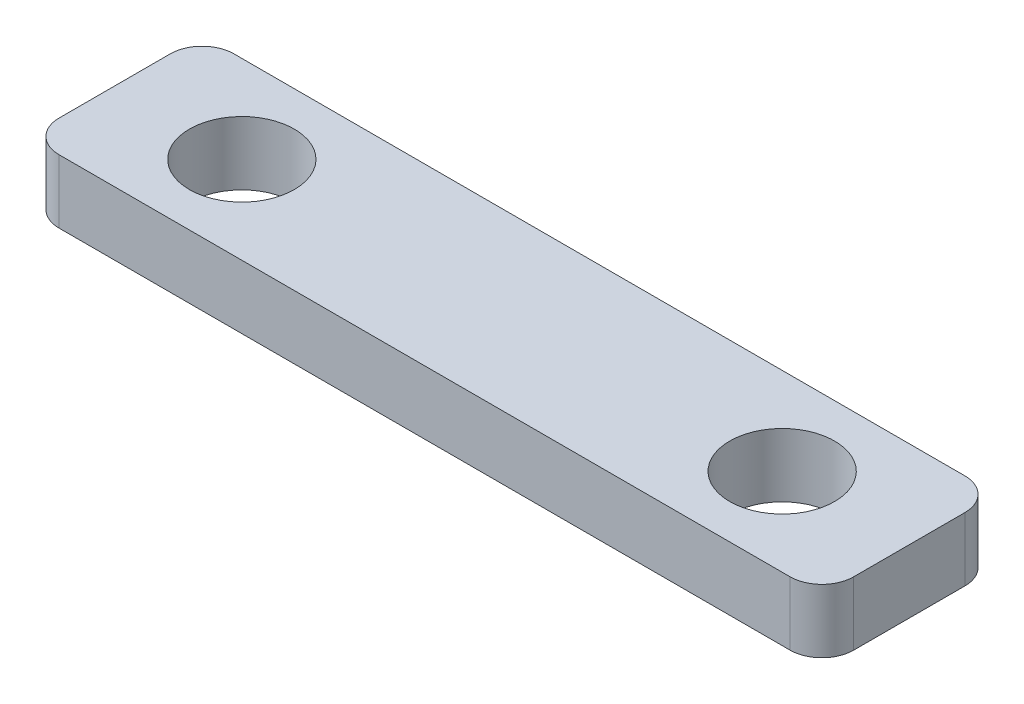
SolidWorks part; units mm, degrees
material "Beryllium Copper, UNS C17000"
ref_plane "Front Plane" through (0, 0, 0) normal (0, 0, 1) x (1, 0, 0)
ref_plane "Top Plane" through (0, 0, 0) normal (0, 1, 0) x (1, 0, 0)
ref_plane "Right Plane" through (0, 0, 0) normal (1, 0, 0) x (0, 0, -1)
sketch "Sketch1" plane through (0, 0, 0) normal (0, 1, 0) x (1, 0, 0)
  line L0 (4, 2.75) -> (21, 2.75) construction
  line L1 (0, 0) -> (25, 0)
  line L2 (0, 0) -> (0, 5.5)
  line L3 (0, 5.5) -> (25, 5.5)
  line L4 (25, 0) -> (25, 5.5)
  line L5 (21, 2.75) -> (25, 2.75) construction
  line L6 (4, 2.75) -> (0, 2.75) construction
  circle A0 centre (4, 2.75) radius 1.65
  circle A1 centre (21, 2.75) radius 1.65
  dimension "D1" = 3.3
  dimension "D2" = 4
  dimension "D3" = 5.5
  dimension "D4" = 25
extrude "Boss-Extrude1" add sketch "Sketch1" along normal blind 2
fillet "Fillet1" radius 1 4 edges at (0, 1, -5.5) (25, 1, -5.5) (25, 1, 0) (0, 1, 0)
